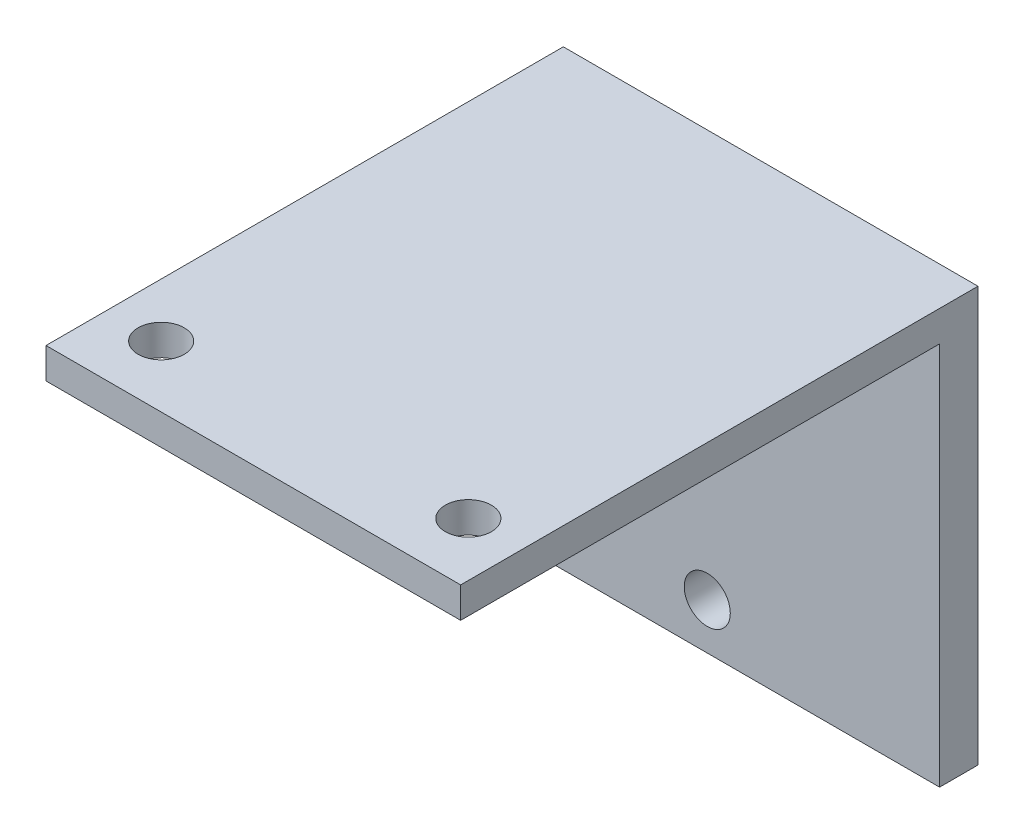
SolidWorks part; units mm, degrees
ref_plane "Plan de face" through (0, 0, 0) normal (0, 0, 1) x (1, 0, 0)
ref_plane "Plan de dessus" through (0, 0, 0) normal (0, 1, 0) x (1, 0, 0)
ref_plane "Plan de droite" through (0, 0, 0) normal (1, 0, 0) x (0, 0, -1)
sketch "Esquisse1" plane through (0, 0, 0) normal (0, 0, 1) x (1, 0, 0)
  line L1 (-27, -27) -> (27, -27)
  line L2 (-27, -27) -> (-27, 27)
  line L3 (-27, 27) -> (27, 27)
  line L4 (27, -27) -> (27, 27)
  line L5 (-27, -27) -> (27, 27) construction
  line L6 (-27, 27) -> (27, -27) construction
  line L7 (9, -27) -> (-9, -27)
  line L8 (9, -27) -> (9, 27)
  line L9 (9, 27) -> (-9, 27)
  line L10 (-9, -27) -> (-9, 27)
  line L11 (9, -27) -> (-9, 27) construction
  line L12 (9, 27) -> (-9, -27) construction
  circle A0 centre (-3.2581, 19) radius 3
  circle A1 centre (-3.2581, -21) radius 3
  point P0 (0, 0)
  point P7 (0, 0)
  dimension "D4" = 6
  dimension "D1" = 54
  dimension "D2" = 54
  dimension "D3" = 18
  dimension "D5" = 8
  dimension "D6" = 5.7419
  dimension "D7" = 2
extrude "Boss.-Extru.1" add sketch "Esquisse1" along normal blind 67.37 contours L8 L1 L4 L3 | L1 L10 L3 L2 | L10 L1 L8 L3 A1 A0
sketch "Esquisse2" plane through (0, 0, 67.37) normal (0, 0, 1) x (1, 0, 0)
  line L8 (23, 23) -> (-23, 23)
  line L9 (-23, 23) -> (-23, -23)
  line L10 (-23, -23) -> (23, -23)
  line L11 (23, -23) -> (23, 23)
  line L12 (38.775, 23) -> (-47.1129, 23)
  line L13 (-47.1129, 23) -> (-47.1129, -35.7903)
  line L14 (-47.1129, -35.7903) -> (38.775, -35.7903)
  line L15 (38.775, -35.7903) -> (38.775, 23)
  dimension "D1" = 4
extrude "Enlèv. mat.-Extru.1" cut sketch "Esquisse2" against normal blind 62.37
sketch "Esquisse3" plane through (0, 23, 0) normal (0, -1, 0) x (1, 0, 0)
  line L0 (27, 67.37) -> (-27, 67.37) construction
  line L1 (-27, 67.37) -> (-27, 5) construction
  circle A0 centre (-20, 59.37) radius 3
  circle A1 centre (20, 59.37) radius 3
  dimension "D3" = 6
  dimension "D1" = 8
  dimension "D2" = 7
  dimension "D4" = 2
extrude "Enlèv. mat.-Extru.2" cut sketch "Esquisse3" against normal blind 62.37
